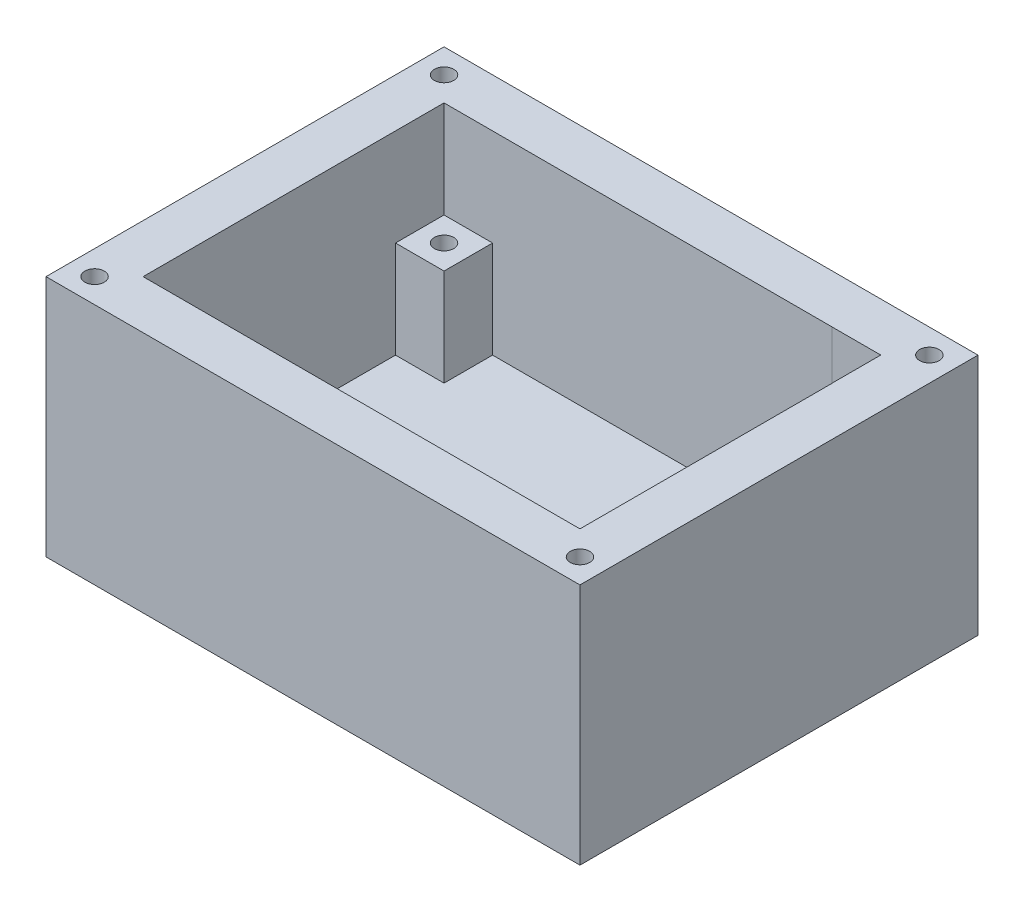
SolidWorks part; units mm, degrees
ref_plane "Front Plane" through (0, 0, 0) normal (0, 0, 1) x (1, 0, 0)
ref_plane "Top Plane" through (0, 0, 0) normal (0, 1, 0) x (1, 0, 0)
ref_plane "Right Plane" through (0, 0, 0) normal (1, 0, 0) x (0, 0, -1)
sketch "Sketch2" plane through (0, 0, 0) normal (0, 1, 0) x (1, 0, 0)
  line L1 (0, 0) -> (-55, 0)
  line L2 (0, 0) -> (0, 5)
  line L3 (0, 5) -> (-55, 5)
  line L4 (-55, 0) -> (-55, 5)
  line L5 (-55, 5) -> (-50, 5)
  line L6 (-55, 5) -> (-55, 41)
  line L7 (-55, 41) -> (-50, 41)
  line L8 (-50, 5) -> (-50, 41)
  line L9 (0, 5) -> (-5, 5)
  line L10 (0, 5) -> (0, 41)
  line L11 (0, 41) -> (-5, 41)
  line L12 (-5, 5) -> (-5, 41)
  line L13 (-50, 5) -> (-45, 5)
  line L14 (-50, 5) -> (-50, 10)
  line L15 (-50, 10) -> (-45, 10)
  line L16 (-45, 5) -> (-45, 10)
  line L17 (-50, 41) -> (-5, 41)
  line L18 (-50, 41) -> (-50, 36)
  line L19 (-50, 36) -> (-5, 36)
  line L20 (-5, 41) -> (-5, 36)
  line L21 (-50, 36) -> (-45, 36)
  line L22 (-50, 36) -> (-50, 31)
  line L23 (-50, 31) -> (-45, 31)
  line L24 (-45, 36) -> (-45, 31)
  line L25 (-5, 36) -> (-9.3303, 36)
  line L26 (-5, 36) -> (-5, 30.9979)
  line L29 (-9.3303, 36) -> (-5, 36)
  line L32 (-5, 36) -> (-5, 30.9979)
  line L33 (-5, 36) -> (-10.0137, 36)
  line L34 (-5, 36) -> (-5, 30.9979)
  line L35 (-5, 30.9979) -> (-10.0137, 30.9979)
  line L36 (-10.0137, 36) -> (-10.0137, 30.9979)
  line L37 (-5, 5) -> (-10, 5)
  line L38 (-5, 5) -> (-5, 10)
  line L39 (-5, 10) -> (-10, 10)
  line L40 (-10, 5) -> (-10, 10)
  dimension "D1" = 55
  dimension "D2" = 36
  dimension "D3" = 5
  dimension "D4" = 5
extrude "Boss-Extrude3" add sketch "Sketch2" along normal blind 20 contours L4 L1 L2 L3 | L12 L3 L10 L11 | L8 L19 L12 L17 | L3 L8 L7 L6 | L24 L19 L8 L23 | L3 L16 L15 L8 | L19 L36 L35 L12 | L40 L3 L12 L39
sketch "Sketch3" plane through (0, 20, 0) normal (0, 1, 0) x (1, 0, 0)
  line L0 (-10.0137, 36) -> (-10.0137, 30.9979) construction
  line L1 (-10.0137, 30.9979) -> (-5.0137, 30.9979)
  line L2 (-10.0137, 30.9979) -> (-10.0137, 35.9979)
  line L3 (-10.0137, 35.9979) -> (-5.0137, 35.9979)
  line L4 (-5.0137, 30.9979) -> (-5.0137, 35.9979)
  dimension "D1" = 5
  dimension "D2" = 5
extrude "Cut-Extrude1" cut sketch "Sketch3" against normal blind 10
sketch "Sketch5" plane through (0, 20, 0) normal (0, 1, 0) x (1, 0, 0)
  line L1 (-45, 31) -> (-50, 31)
  line L2 (-45, 31) -> (-45, 36)
  line L3 (-45, 36) -> (-50, 36)
  line L4 (-50, 31) -> (-50, 36)
  dimension "D1" = 5
  dimension "D2" = 5
extrude "Cut-Extrude2" cut sketch "Sketch5" against normal blind 10
sketch "Sketch6" plane through (0, 20, 0) normal (0, 1, 0) x (1, 0, 0)
  line L1 (-45, 10) -> (-50, 10)
  line L2 (-45, 10) -> (-45, 5)
  line L3 (-45, 5) -> (-50, 5)
  line L4 (-50, 10) -> (-50, 5)
  line L5 (-10, 10) -> (-5, 10)
  line L6 (-10, 10) -> (-10, 5)
  line L7 (-10, 5) -> (-5, 5)
  line L8 (-5, 10) -> (-5, 5)
  dimension "D1" = 5
  dimension "D2" = 5
  dimension "D3" = 5
  dimension "D4" = 5
extrude "Cut-Extrude3" cut sketch "Sketch6" against normal blind 10
sketch "Sketch7" plane through (0, 10, 0) normal (0, 1, 0) x (1, 0, 0)
  circle A1 centre (-47.5, 33.5) radius 1
extrude "Cut-Extrude5" cut sketch "Sketch7" against normal blind 10
sketch "Sketch8" plane through (0, 10, 0) normal (0, 1, 0) x (1, 0, 0)
  circle A0 centre (-7.5137, 33.4979) radius 1
extrude "Cut-Extrude6" cut sketch "Sketch8" against normal blind 10
sketch "Sketch9" plane through (0, 10, 0) normal (0, 1, 0) x (1, 0, 0)
  circle A0 centre (-47.5, 7.5) radius 1
extrude "Cut-Extrude7" cut sketch "Sketch9" against normal blind 10
sketch "Sketch10" plane through (0, 10, 0) normal (0, 1, 0) x (1, 0, 0)
  circle A0 centre (-7.5, 7.5) radius 1
extrude "Cut-Extrude8" cut sketch "Sketch10" against normal blind 10
sketch "Sketch11" plane through (0, 0, 0) normal (0, -1, 0) x (-1, 0, 0)
  line L1 (55, 0) -> (0, 0)
  line L2 (55, 0) -> (55, 41)
  line L3 (55, 41) -> (0, 41)
  line L4 (0, 0) -> (0, 41)
extrude "Boss-Extrude10" add sketch "Sketch11" along normal blind 5
sketch "Sketch12" plane through (0, 20, 0) normal (0, 1, 0) x (1, 0, 0)
  circle A0 centre (-52.5, 38.5) radius 1
extrude "Cut-Extrude9" cut sketch "Sketch12" against normal blind 10
sketch "Sketch13" plane through (0, 20, 0) normal (0, 1, 0) x (1, 0, 0)
  line L1 (0, 41) -> (-5.0137, 41)
  line L2 (0, 41) -> (0, 35.9979)
  line L3 (0, 35.9979) -> (-5.0137, 35.9979)
  circle A0 centre (-2.5068, 38.499) radius 1
extrude "Cut-Extrude10" cut sketch "Sketch13" against normal blind 10 contours A0
sketch "Sketch14" plane through (0, 20, 0) normal (0, 1, 0) x (1, 0, 0)
  circle A0 centre (-52.5, 2.5) radius 1
extrude "Cut-Extrude11" cut sketch "Sketch14" against normal blind 10
sketch "Sketch15" plane through (0, 20, 0) normal (0, 1, 0) x (1, 0, 0)
  circle A0 centre (-2.5, 2.5) radius 1
extrude "Cut-Extrude12" cut sketch "Sketch15" against normal blind 10
